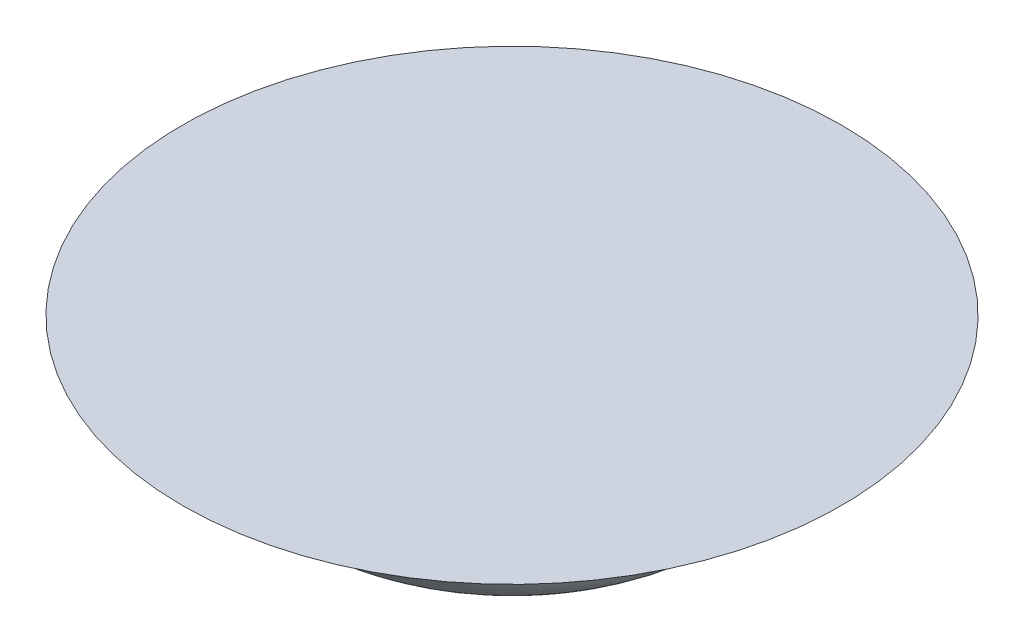
SolidWorks part; units mm, degrees
ref_plane "Plane1" through (0, 0, 0) normal (0, 0, 1) x (1, 0, 0)
ref_plane "Plane2" through (0, 0, 0) normal (0, 1, 0) x (1, 0, 0)
ref_plane "Plane3" through (0, 0, 0) normal (1, 0, 0) x (0, 0, -1)
sketch "Sketch1" plane through (0, 0, 0) normal (0, 0, 1) x (1, 0, 0)
  line L0 (-101.8453, 0) -> (101.8453, 0)
  line L1 (-101.8453, 0) -> (-101.8453, 2)
  line L2 (101.8453, 2) -> (-101.8453, 2)
  line L3 (101.8453, 2) -> (101.8453, 0)
  line L4 (50, 0) -> (-50, 0) construction
  line L5 (0, -25.996) -> (0, 39.4685) construction
  dimension "D1" = 2
extrude "Base-Extrude" add sketch "Sketch1" along normal mid plane 120
sketch "Sketch3" plane through (0, 0, 0) normal (0, -1, 0) x (1, 0, 0)
  circle A0 centre (0, 0) radius 10
  dimension "Diameter" = 20
extrude "Boss-Extrude1" add sketch "Sketch3" along normal blind 5
fillet "Fillet" radius 3 1 edges at (0, -5, -10)
fillet "Fillet2" radius 5 1 edges at (0, 0, 10)
sketch "Sketch4" plane through (101.8453, 0, 0) normal (1, 0, 0) x (0, 0, -1)
  line L4 (60, 0) -> (60, 2)
  line L5 (60, 2) -> (-60, 2)
  line L6 (-60, 2) -> (-60, 0)
  line L7 (-60, 0) -> (60, 0)
  line L8 (60, 0) -> (60, 2)
  line L9 (60, 2) -> (-60, 2)
  line L10 (-60, 2) -> (-60, 0)
  line L11 (-60, 0) -> (60, 0)
  dimension "D1" = 0
extrude "Cut-Extrude1" cut sketch "Sketch4" against normal through all
sketch "Orientation sketch" plane through (0, 0, 0) normal (0, 1, 0) x (-1, 0, 0)
  circle A1 centre (0, 0) radius 14.4162
  circle A2 centre (0, 0) radius 14.4162
  dimension "D1" = 0
